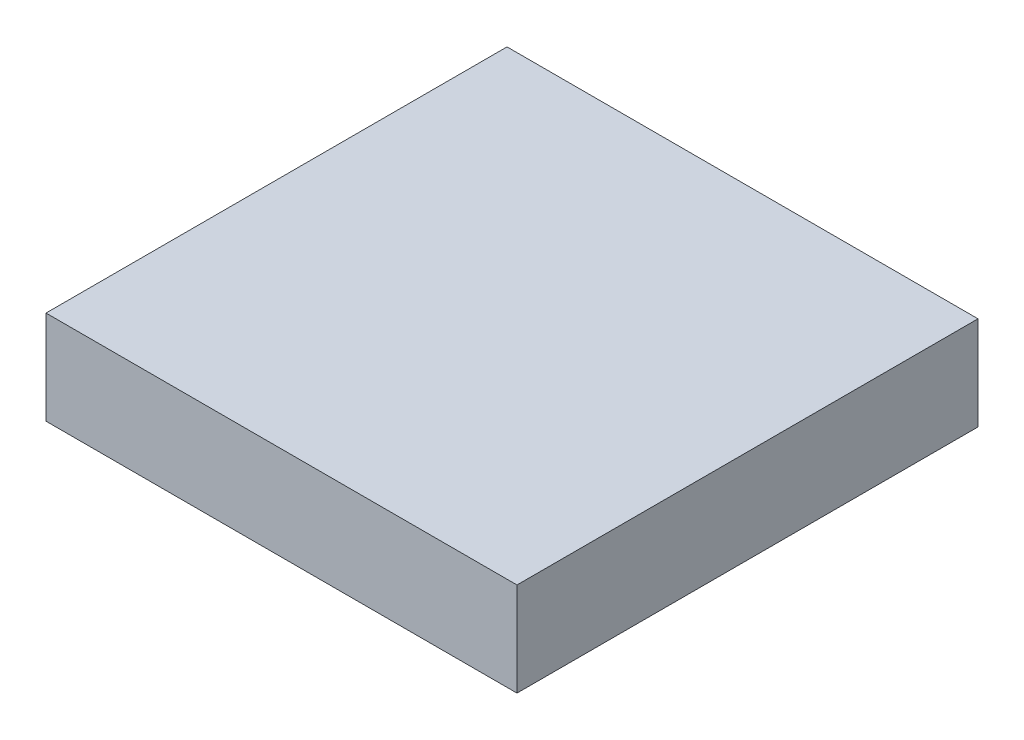
SolidWorks part; units mm, degrees
ref_plane "Front Plane" through (0, 0, 0) normal (0, 0, 1) x (1, 0, 0)
ref_plane "Top Plane" through (0, 0, 0) normal (0, 1, 0) x (1, 0, 0)
ref_plane "Right Plane" through (0, 0, 0) normal (1, 0, 0) x (0, 0, -1)
sketch "Sketch1" plane through (0, 0, 0) normal (0, 0, 1) x (1, 0, 0)
  line L0 (-0.46, 0.2716) -> (0.5616, 0.2716)
  line L1 (0.5616, 0.2716) -> (0.5616, 0.0684)
  line L2 (0.5616, 0.0684) -> (-0.46, 0.0684)
  line L3 (-0.46, 0.0684) -> (-0.46, 0.2716)
extrude "Component_Outline" add sketch "Sketch1" along normal blind 1 separate body
sketch3d "3DSketch1"
  line L0 (0, 0, 0) -> (1, 0, 0)
  line L1 (0, 0, 0) -> (0, 1, 0)
  line L2 (0, 0, 0) -> (0, 0, 1)
  point P0 (0, 0, 0)
